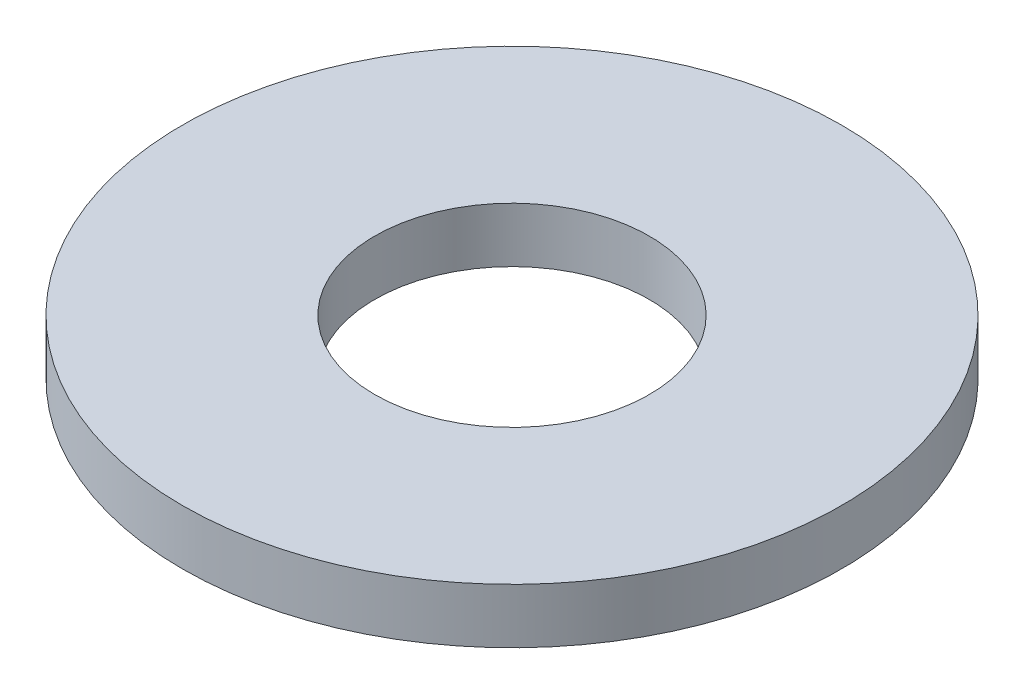
SolidWorks part; units mm, degrees
ref_plane "Front Plane" through (0, 0, 0) normal (0, 0, 1) x (1, 0, 0)
ref_plane "Top Plane" through (0, 0, 0) normal (0, 1, 0) x (1, 0, 0)
ref_plane "Right Plane" through (0, 0, 0) normal (1, 0, 0) x (0, 0, -1)
sketch "Sketch1" plane through (0, 0, 0) normal (0, 1, 0) x (1, 0, 0)
  circle A0 centre (0, 0) radius 3.175
  circle A1 centre (0, 0) radius 7.62
  dimension "D1" = 6.35
  dimension "D2" = 15.24
extrude "Boss-Extrude1" add sketch "Sketch1" along normal blind 1.27
